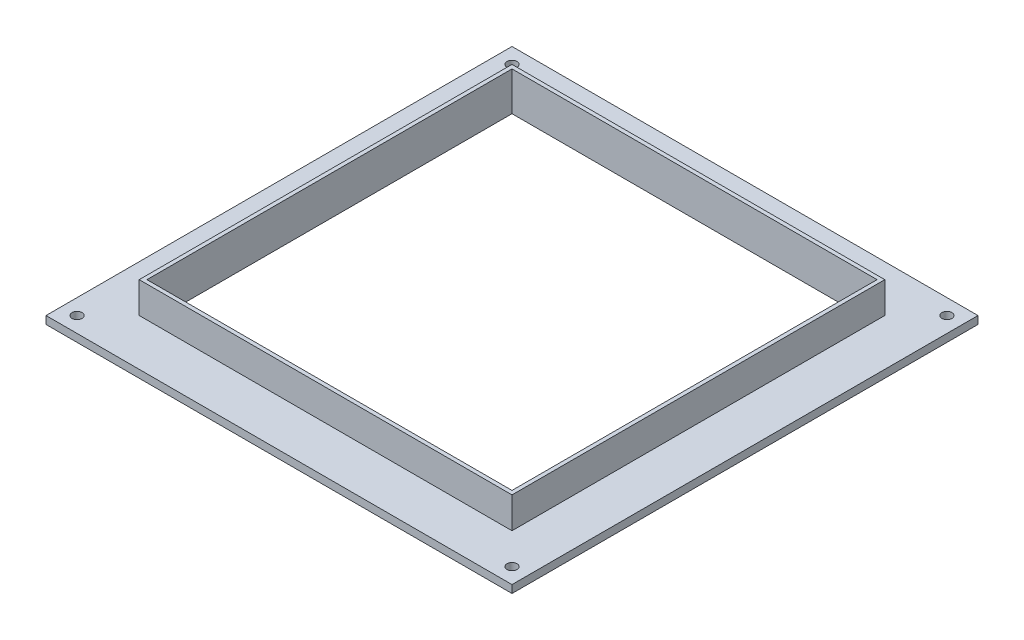
SolidWorks part; units mm, degrees
ref_plane "Front Plane" through (0, 0, 0) normal (0, 0, 1) x (1, 0, 0)
ref_plane "Top Plane" through (0, 0, 0) normal (0, 1, 0) x (1, 0, 0)
ref_plane "Right Plane" through (0, 0, 0) normal (1, 0, 0) x (0, 0, -1)
sketch "Sketch3" plane through (0, 0, 0) normal (0, 1, 0) x (1, 0, 0)
  line L0 (0, 0) -> (300, 300)
  line L1 (0, 0) -> (300, 0)
  line L2 (0, 0) -> (0, 300)
  line L3 (0, 300) -> (300, 300)
  line L4 (300, 0) -> (300, 300)
  line L5 (300, 0) -> (0, 300)
  dimension "D1" = 300
  dimension "D2" = 300
extrude "Boss-Extrude1" add sketch "Sketch3" along normal blind 5 contours L5 L4 L0 | L1 L5 L0 | L0 L5 L2 | L5 L0 L3
sketch "Sketch4" plane through (0, 5, 0) normal (0, 1, 0) x (1, 0, 0)
  line L0 (0, 0) -> (300, 300)
  line L1 (0, 300) -> (300, 0)
  line L5 (30, 30) -> (270, 30)
  line L6 (30, 30) -> (30, 270)
  line L7 (30, 270) -> (270, 270)
  line L8 (270, 30) -> (270, 270)
  line L9 (30, 30) -> (270, 270) construction
  line L10 (30, 270) -> (270, 30) construction
  line L11 (34.75, 34.75) -> (265.25, 34.75)
  line L12 (34.75, 34.75) -> (34.75, 265.25)
  line L13 (34.75, 265.25) -> (265.25, 265.25)
  line L14 (265.25, 34.75) -> (265.25, 265.25)
  line L15 (34.75, 34.75) -> (265.25, 265.25) construction
  line L16 (34.75, 265.25) -> (265.25, 34.75) construction
  point P8 (150, 150)
  point P12 (150, 150)
  dimension "D1" = 240
  dimension "D2" = 240
  dimension "D3" = 230.5
  dimension "D4" = 230.5
extrude "Boss-Extrude2" add sketch "Sketch4" along normal blind 20 contours L12 L13 L14 L11 | L6 L7 L8 L5
sketch "Sketch6" plane through (0, 5, 0) normal (0, 1, 0) x (1, 0, 0)
  line L0 (0, 0) -> (10, 0)
  line L1 (0, 0) -> (300, 0) construction
  line L2 (10, 0) -> (10, 10)
  line L3 (10, 10) -> (290, 10)
  line L4 (290, 10) -> (290, 290)
  line L5 (290, 290) -> (10, 290)
  circle A0 centre (10, 10) radius 3.25
  circle A1 centre (290, 10) radius 3.25
  circle A2 centre (290, 290) radius 3.25
  circle A3 centre (10, 290) radius 3.25
  dimension "D1" = 6.5
  dimension "D3" = 6.5
  dimension "D5" = 6.5
  dimension "D6" = 6.5
  dimension "D2" = 280
  dimension "D4" = 280
extrude "Cut-Extrude1" cut sketch "Sketch6" against normal blind 20
sketch "Sketch7" plane through (0, 25, 0) normal (0, 1, 0) x (1, 0, 0)
  line L2 (30, 30) -> (270, 30)
  line L3 (30, 30) -> (30, 270)
  line L4 (30, 270) -> (270, 270)
  line L5 (270, 30) -> (270, 270)
extrude "Cut-Extrude2" cut sketch "Sketch7" against normal blind 20
sketch "Sketch8" plane through (0, 5, 0) normal (0, 1, 0) x (1, 0, 0)
  line L0 (30, 30) -> (270, 30)
  line L1 (0, 0) -> (32.5, 0)
  line L2 (0, 0) -> (300, 0) construction
  line L3 (32.5, 0) -> (32.5, 32.5)
  line L4 (270, 30) -> (270, 270)
  line L5 (32.5, 32.5) -> (267.5, 32.5)
  line L6 (32.5, 32.5) -> (32.5, 267.5)
  line L7 (32.5, 267.5) -> (267.5, 267.5)
  line L8 (267.5, 32.5) -> (267.5, 267.5)
  line L9 (30, 270) -> (270, 270)
  line L10 (30, 30) -> (30, 270)
  dimension "D1" = 235
  dimension "D2" = 235
  dimension "D4" = 240
  dimension "D5" = 240
  dimension "D3" = 2.5
extrude "Boss-Extrude3" add sketch "Sketch8" along normal blind 20
sketch "Sketch9" plane through (0, 5, 0) normal (0, 1, 0) x (1, 0, 0)
  line L1 (32.5, 32.5) -> (267.5, 32.5)
  line L2 (32.5, 32.5) -> (32.5, 267.5)
  line L3 (32.5, 267.5) -> (267.5, 267.5)
  line L4 (267.5, 32.5) -> (267.5, 267.5)
extrude "Cut-Extrude3" cut sketch "Sketch9" against normal blind 20
